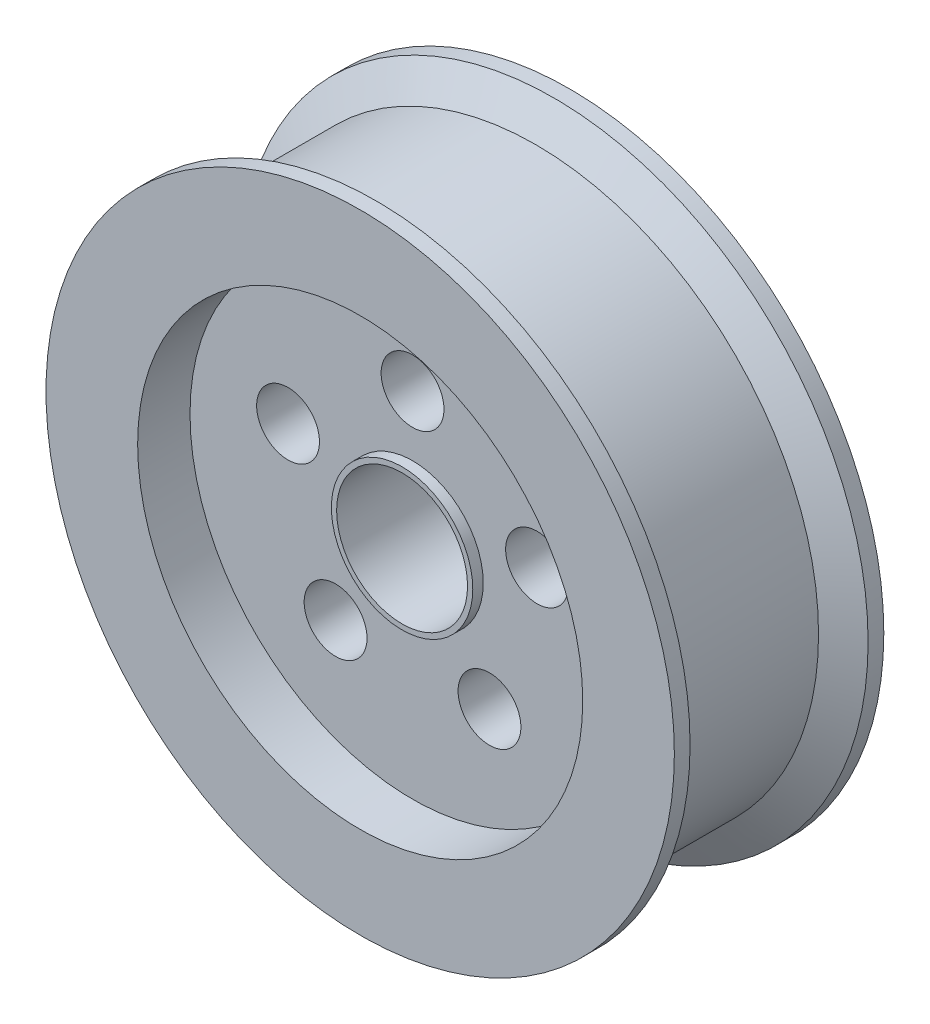
SolidWorks part; units mm, degrees
material "AISI 1015 Steel, Cold Drawn (SS)"
ref_plane "Front Plane" through (0, 0, 0) normal (0, 0, 1) x (1, 0, 0)
ref_plane "Top Plane" through (0, 0, 0) normal (0, 1, 0) x (1, 0, 0)
ref_plane "Right Plane" through (0, 0, 0) normal (1, 0, 0) x (0, 0, -1)
sketch "Sketch2" plane through (0, 0, 0) normal (0, 0, 1) x (1, 0, 0)
  circle A0 centre (0, 0) radius 60
  circle A1 centre (0, 0) radius 12.5
  dimension "D1" = 120
  dimension "D2" = 25
extrude "Boss-Extrude1" add sketch "Sketch2" along normal mid plane 40
sketch "Sketch3" plane through (0, 0, 20) normal (0, 0, 1) x (1, 0, 0)
  circle A0 centre (0, 0) radius 42.5
  dimension "D1" = 85
extrude "Cut-Extrude1" cut sketch "Sketch3" against normal blind 10
mirror "Mirror2" about plane through (0, 0, 0) normal (0, 0, 1) of "Cut-Extrude1"
sketch "Sketch4" plane through (0, 0, 10) normal (0, 0, 1) x (1, 0, 0)
  circle A0 centre (0, 25) radius 6
  dimension "D1" = 12
  dimension "D2" = 25
extrude "Cut-Extrude2" cut sketch "Sketch4" against normal through all both and the other way through all
pattern_circular "CirPattern2" count 5 over 360 about axis through (0, 0, 0) along (0, 0, 1) of "Cut-Extrude2"
sketch "Sketch5" plane through (0, 0, 0) normal (0, 1, 0) x (1, 0, 0)
  line L0 (0, 0) -> (0, 28.6742) construction
  line L1 (54, 13.5359) -> (60, 17)
  line L2 (60, -20) -> (60, 20) construction
  line L3 (60, 17) -> (60, -17)
  line L4 (60, -17) -> (54, -13.5359)
  line L5 (54, -13.5359) -> (54, 13.5359)
  line L6 (60, 20) -> (-60, 20) construction
  line L7 (-60, -20) -> (60, -20) construction
  dimension "D1" = 6
  dimension "D2" = 3
  dimension "D3" = 3
  dimension "D4" = 60
  dimension "D5" = 60
revolve "Cut-Revolve1" cut sketch "Sketch5" angle 360 about L0
sketch "Sketch6" plane through (0, 0, 10) normal (0, 0, 1) x (1, 0, 0)
  circle A0 centre (0, 0) radius 13.5
  circle A1 centre (0, 0) radius 12.5 construction
  circle A2 centre (0, 0) radius 12.5
  dimension "D1" = 27
extrude "Boss-Extrude3" add sketch "Sketch6" along normal blind 2 and the other way blind 7
